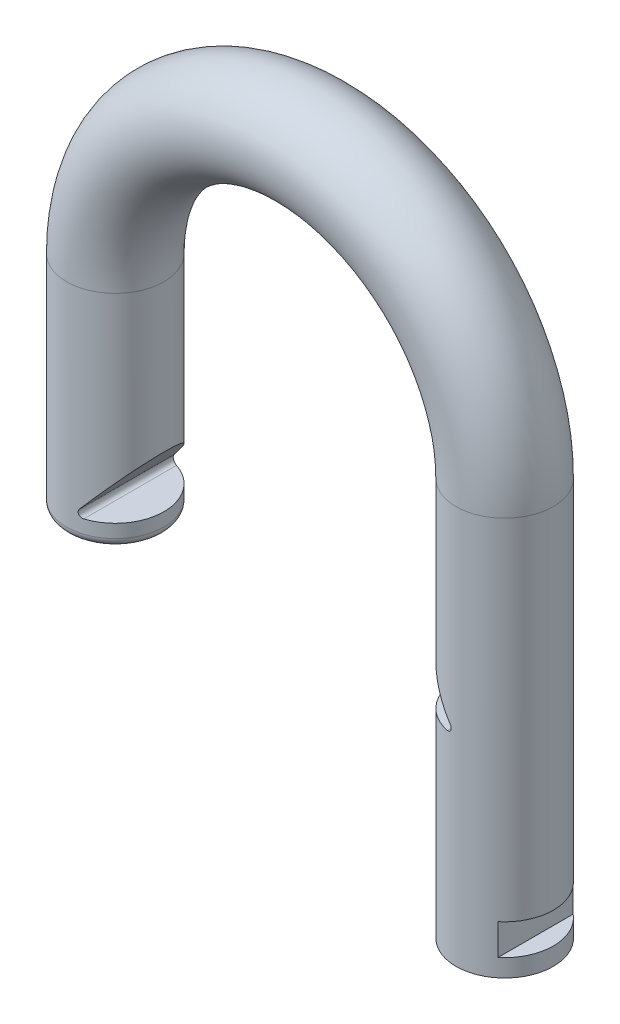
SolidWorks part; units mm, degrees
ref_plane "前视基准面" through (0, 0, 0) normal (0, 0, 1) x (1, 0, 0)
ref_plane "上视基准面" through (0, 0, 0) normal (0, 1, 0) x (1, 0, 0)
ref_plane "右视基准面" through (0, 0, 0) normal (1, 0, 0) x (0, 0, -1)
other "Configuration Table"
sketch "草图2" plane through (0, 0, 0) normal (0, 0, 1) x (1, 0, 0)
  line L0 (-22, 22) -> (11.1485, 22) construction
  line L1 (-22, 0) -> (-22, -25)
  line L2 (22, 0) -> (22, -45)
  arc A0 (22, 0) -> (-22, 0) centre (0, 0) ccw
  dimension "D1" = 22
  dimension "D2" = 47
  dimension "D3" = 67
sweep "扫描1" add path "草图2" circular profile diameter 11 parameters "D3"=11
fillet "圆角1" radius 1 1 edges at (-16.5, -25, 0)
sketch "草图10" plane through (0, 0, 0) normal (0, 0, 1) x (1, 0, 0)
  line L0 (-16.5, -22.5) -> (-21.3969, -22.5)
  line L1 (-16.5, -24) -> (-16.5, 0) construction
  line L2 (-21.3969, -22.5) -> (-16.5, -16.6641)
  line L3 (-26.5, -25) -> (-17.5, -25) construction
  line L4 (-16.5, -16.6641) -> (-16.5, -22.5)
  dimension "D1" = 50
  dimension "D2" = 2.5
extrude "切除-拉伸1" cut sketch "草图10" against normal through all both and the other way through all
fillet "圆角2" radius 0.5 1 edges at (-21.3969, -22.5, 0)
sketch "草图11" plane through (0, 0, 0) normal (0, 0, 1) x (1, 0, 0)
  line L0 (27.5, -43) -> (25.5, -43)
  line L1 (27.5, -45) -> (27.5, 0) construction
  line L2 (25.5, -43) -> (25.5, -39.5)
  line L3 (25.5, -39.5) -> (27.5, -39.5)
  line L4 (16.5, -45) -> (27.5, -45) construction
  line L5 (22, -45) -> (22, -39.2755) construction
  line L6 (16.5, -43) -> (18.5, -43)
  line L7 (18.5, -43) -> (18.5, -39.5)
  line L8 (18.5, -39.5) -> (16.5, -39.5)
  line L9 (16.5, -39.5) -> (16.5, -43)
  line L10 (27.5, -39.5) -> (27.5, -43)
  dimension "D1" = 3.5
  dimension "D2" = 2
  dimension "D3" = 2
extrude "切除-拉伸2" cut sketch "草图11" against normal through all both and the other way through all
sketch "草图12" plane through (0, 0, 0) normal (0, 0, 1) x (1, 0, 0)
  line L0 (18.5, -39.5) -> (18.5, -28.5)
  line L1 (18.5, -28.5) -> (16.5, -27.3453)
  line L2 (16.5, 0) -> (16.5, -39.5) construction
  line L3 (16.5, -27.3453) -> (16.5, -39.5)
  line L4 (16.5, -39.5) -> (18.5, -39.5)
  dimension "D1" = 11
  dimension "D2" = 120
extrude "切除-拉伸3" cut sketch "草图12" against normal through all both and the other way through all
sketch "草图13" plane through (0, 0, 0) normal (0, 0, 1) x (1, 0, 0)
  line L0 (16.5, -22.5) -> (22, -22.5)
  line L2 (16.5, 0) -> (16.5, -27.3453) construction
  line L3 (22, -22.5) -> (16.5, -15.9454)
  line L4 (16.5, -15.9454) -> (16.5, -22.5)
  dimension "D1" = 5.5
  dimension "D2" = 50
extrude "切除-拉伸4" cut sketch "草图13" against normal through all both and the other way through all
fillet "圆角3" radius 0.5 1 edges at (22, -22.5, 0)
